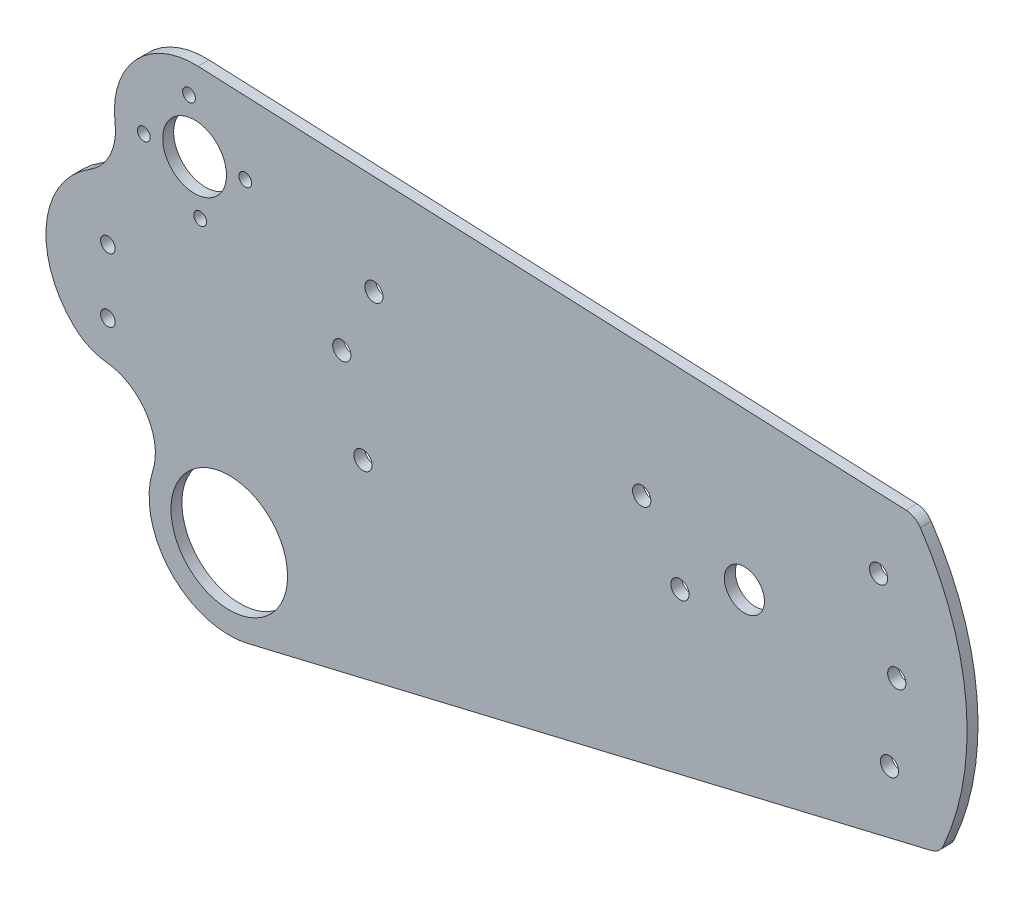
SolidWorks part; units mm, degrees
ref_plane "Front Plane" through (0, 0, 0) normal (0, 0, 1) x (1, 0, 0)
ref_plane "Top Plane" through (0, 0, 0) normal (0, 1, 0) x (1, 0, 0)
ref_plane "Right Plane" through (0, 0, 0) normal (1, 0, 0) x (0, 0, -1)
sketch "Sketch1" plane through (0, 0, 0) normal (0, 0, 1) x (1, 0, 0)
  line L0 (83.305, -33.5) -> (-137.2004, -33.5) construction
  line L1 (-113.5603, 49.4797) -> (80.7216, 41.1353)
  line L2 (-116.9253, 49.6243) -> (-102.5652, -81.605) construction
  line L3 (-99.3111, -80.7362) -> (92.6556, -29.4815) construction
  line L4 (75.1114, 41.3762) -> (83.1431, -32.0213) construction
  line L5 (-109.7453, -15.9904) -> (79.1273, 4.6775) construction
  line L6 (91, -33.5) -> (-88.5, -33.5) construction
  line L7 (-97.4673, 5.5) -> (-155.3054, 5.5) construction
  line L8 (-138.3, -14) -> (-155.3054, -14) construction
  line L9 (-138.3, 5.5) -> (-138.3, -33.5) construction
  line L10 (-155.3054, 5.5) -> (-155.3054, -33.5) construction
  line L11 (36.3824, 33.5) -> (36.3824, -33.5) construction
  line L12 (-111.638, -83.6744) -> (87.5903, -36.3264)
  line L13 (-91.5, 33.5) -> (88, 33.5) construction
  line L14 (-68.3, -21.5) -> (-108.6591, -25.9164) construction
  circle A0 centre (36.3824, 0) radius 5.5
  circle A1 centre (-114.5043, 27.5) radius 14 construction
  circle A2 centre (-104.9862, -59.4808) radius 14 construction
  arc A3 (-91.5, 33.5) -> (-88.5, -33.5) centre (-18.0922, 3.2198) ccw construction
  circle A4 centre (-68.3, -21.5) radius 2.5
  circle A5 centre (-68.3, -21.5) radius 2.5 construction
  circle A6 centre (-138.3, -5.25) radius 2
  circle A7 centre (-138.3, -22.75) radius 2
  arc A8 (-143.371, 10.0569) -> (-147.5429, -29.3643) centre (-130.3054, -11.2571) ccw
  arc A9 (-147.5429, -29.3643) -> (-137.2004, -33.5) centre (-137.2004, -18.5) ccw
  circle A10 centre (-114.5043, 27.5) radius 22
  arc A11 (87.5903, -36.3264) -> (91, -33.5) centre (86.4343, -31.4619) ccw
  circle A12 centre (-104.9862, -59.4808) radius 22
  arc A13 (91, -33.5) -> (84.6484, 38.9414) centre (22.6589, -2.9929) ccw
  arc A14 (91, -33.5) -> (88, 33.5) centre (22.6589, -2.9929) ccw construction
  arc A15 (84.6484, 38.9414) -> (80.7216, 41.1353) centre (80.507, 36.1399) ccw
  arc A17 (-125.9657, -52.858) -> (-138.7351, -33.4213) centre (-140.2699, -48.3426) ccw
  arc A18 (-143.371, 10.0569) -> (-136.3295, 24.7324) centre (-151.2104, 22.8454) ccw
  circle A19 centre (-74.1, 1.7) radius 2.5
  circle A20 centre (-65.3, 20) radius 2.5
  circle A21 centre (8.2, 8.3) radius 2.5
  circle A23 centre (18.7, -8.7) radius 2.5
  circle A25 centre (78.2, -0.1) radius 2.5
  circle A26 centre (76.2, -22) radius 2.5
  circle A27 centre (73.2, 22.3) radius 2.5
  circle A28 centre (73.2, 22.3) radius 2.5 construction
  circle A29 centre (78.2, -0.1) radius 2.5 construction
  circle A31 centre (8.2, 8.3) radius 2.5 construction
  circle A32 centre (18.7, -8.7) radius 2.5 construction
  circle A33 centre (76.2, -22) radius 2.5 construction
  circle A34 centre (-74.1, 1.7) radius 2.5 construction
  circle A35 centre (-65.3, 20) radius 2.5 construction
  circle A36 centre (-116.0272, 41.4169) radius 1.75
  circle A37 centre (-100.5874, 29.0229) radius 1.75
  circle A38 centre (-112.9814, 13.5831) radius 1.75
  circle A39 centre (-128.4212, 25.9771) radius 1.75
  circle A40 centre (-106.5091, -45.5639) radius 1.75
  circle A41 centre (-91.0693, -57.9579) radius 1.75
  circle A42 centre (-103.4633, -73.3977) radius 1.75
  circle A43 centre (-118.9031, -61.0037) radius 1.75
  circle A44 centre (36.3824, 0) radius 35 construction
  circle A45 centre (36.3824, 0) radius 43
  circle A49 centre (-104.9862, -59.4808) radius 16
  circle A50 centre (-114.5043, 27.5) radius 16 construction
  circle A51 centre (-114.5043, 27.5) radius 8.75
  circle A52 centre (-104.9862, -59.4808) radius 8.75
  arc A53 (91, -33.5) -> (88, 33.5) centre (22.6589, -2.9929) ccw construction
  point P44 (0, 0)
  point P46 (0, 0)
  point P52 (79.1273, 4.6775)
  point P70 (-111.638, -83.6744)
  point P109 (-114.5043, 27.5)
  point P118 (-104.9862, -59.4808)
  dimension "D5" = 4
  dimension "D6" = 25
  dimension "D9" = 15
  dimension "D13" = 10
  dimension "D14" = 28
  dimension "D11" = 44
  dimension "D15" = 3.5
  dimension "D12" = 70
  dimension "D19" = 11
  dimension "D20" = 17.5
  dimension "D22" = 32
  dimension "D2" = 39
  dimension "D3" = 70
  dimension "D4" = 17.5
  dimension "D7" = 14
  dimension "D8" = 10
  dimension "D10" = 87.5
  dimension "D21" = 190
  dimension "D23" = 40.6
  dimension "D18" = 8
  dimension "D16" = 4
  dimension "D17" = 4
extrude "Boss-Extrude1" add sketch "Sketch1" along normal blind 3
